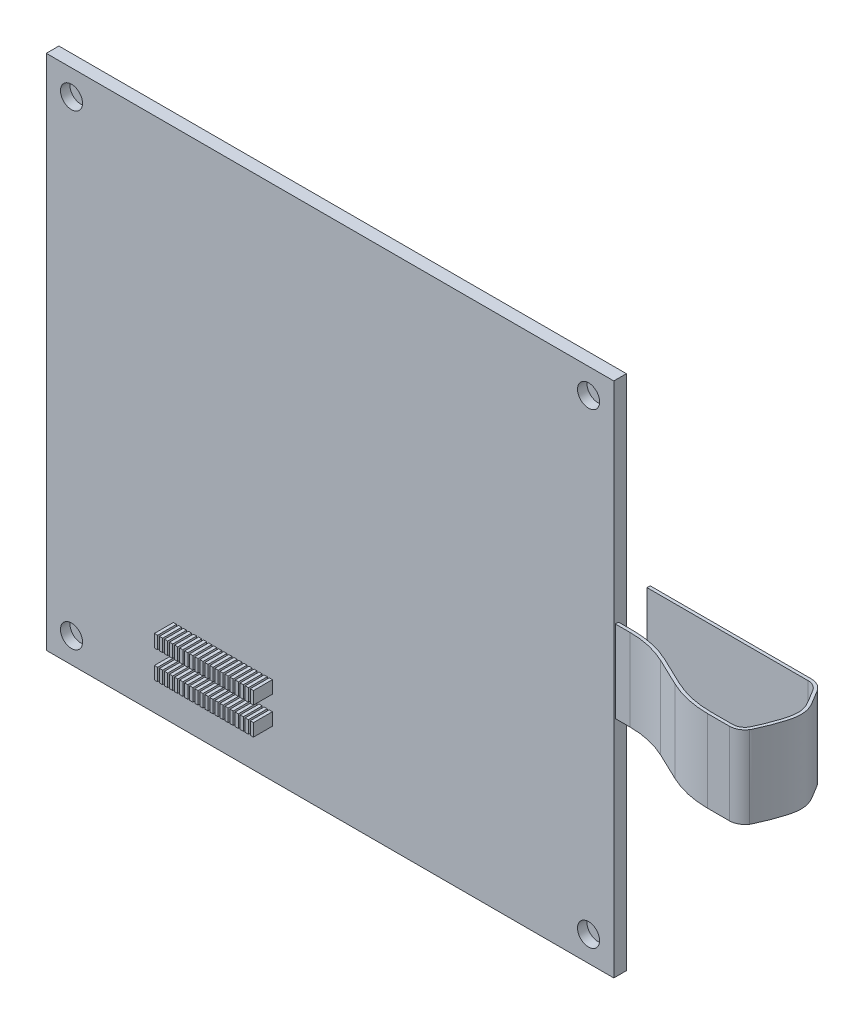
SolidWorks part; units mm, degrees
ref_plane "Face" through (0, 0, 0) normal (0, 0, 1) x (1, 0, 0)
ref_plane "Dessus" through (0, 0, 0) normal (0, 1, 0) x (1, 0, 0)
ref_plane "Droite" through (0, 0, 0) normal (1, 0, 0) x (0, 0, -1)
sketch "Esquisse1" plane through (0, 0, 0) normal (0, 0, 1) x (1, 0, 0)
  line L1 (0, 0) -> (90, 0)
  line L2 (0, 0) -> (0, 82)
  line L3 (0, 82) -> (90, 82)
  line L4 (90, 0) -> (90, 82)
  dimension "D1" = 90
  dimension "D2" = 82
extrude "Base-Extrusion" add sketch "Esquisse1" against normal blind 2
sketch "Esquisse2" plane through (0, 0, 0) normal (0, 0, 1) x (1, 0, 0)
  line L0 (90, 82) -> (0, 82) construction
  line L1 (0, 82) -> (0, 0) construction
  line L2 (90, 0) -> (90, 82) construction
  line L3 (0, 0) -> (90, 0) construction
  circle A0 centre (4, 78) radius 1.75
  circle A1 centre (86, 78) radius 1.75
  circle A2 centre (86, 4) radius 1.75
  circle A3 centre (4, 4) radius 1.75
  dimension "D1" = 3.5
  dimension "D2" = 3.5
  dimension "D3" = 3.5
  dimension "D4" = 3.5
  dimension "D6" = 4
  dimension "D7" = 4
  dimension "D8" = 4
  dimension "D9" = 4
  dimension "D10" = 4
  dimension "D11" = 4
  dimension "D12" = 4
  dimension "D5" = 4
extrude "Enlèv. mat.-Extru.1" cut sketch "Esquisse2" against normal blind 1.5
sketch "Esquisse3" plane through (0, 0, 0) normal (0, 0, 1) x (1, 0, 0)
  line L0 (20.4, 11.361) -> (20.4, 15.0274) construction
  line L1 (18.7961, 12.9) -> (22.2029, 12.9) construction
  line L2 (20.65, 13.9) -> (20.65, 11.9)
  line L3 (20.15, 13.9) -> (20.15, 11.9)
  line L4 (20.15, 13.9) -> (20.65, 13.9)
  line L5 (20.15, 11.9) -> (20.65, 11.9)
  line L6 (14.944, 10.7) -> (26.7013, 10.7) construction
  line L7 (20.15, 7.5) -> (20.65, 7.5)
  line L8 (35.6, 13.9) -> (35.6, 14.4408) construction
  line L10 (20.15, 9.5) -> (20.65, 9.5)
  line L11 (20.65, 9.5) -> (20.65, 7.5)
  line L12 (20.15, 9.5) -> (20.15, 7.5)
  line L13 (21.45, 13.9) -> (21.45, 11.9)
  line L14 (20.95, 13.9) -> (20.95, 11.9)
  line L15 (20.95, 13.9) -> (21.45, 13.9)
  line L16 (20.95, 11.9) -> (21.45, 11.9)
  line L17 (20.95, 7.5) -> (21.45, 7.5)
  line L20 (20.95, 9.5) -> (21.45, 9.5)
  line L21 (21.45, 9.5) -> (21.45, 7.5)
  line L22 (20.95, 9.5) -> (20.95, 7.5)
  line L23 (22.25, 13.9) -> (22.25, 11.9)
  line L24 (21.75, 13.9) -> (21.75, 11.9)
  line L25 (21.75, 13.9) -> (22.25, 13.9)
  line L26 (21.75, 11.9) -> (22.25, 11.9)
  line L27 (21.75, 7.5) -> (22.25, 7.5)
  line L30 (21.75, 9.5) -> (22.25, 9.5)
  line L31 (22.25, 9.5) -> (22.25, 7.5)
  line L32 (21.75, 9.5) -> (21.75, 7.5)
  line L33 (23.05, 13.9) -> (23.05, 11.9)
  line L34 (22.55, 13.9) -> (22.55, 11.9)
  line L35 (22.55, 13.9) -> (23.05, 13.9)
  line L36 (22.55, 11.9) -> (23.05, 11.9)
  line L37 (22.55, 7.5) -> (23.05, 7.5)
  line L40 (22.55, 9.5) -> (23.05, 9.5)
  line L41 (23.05, 9.5) -> (23.05, 7.5)
  line L42 (22.55, 9.5) -> (22.55, 7.5)
  line L43 (23.85, 13.9) -> (23.85, 11.9)
  line L44 (23.35, 13.9) -> (23.35, 11.9)
  line L45 (23.35, 13.9) -> (23.85, 13.9)
  line L46 (23.35, 11.9) -> (23.85, 11.9)
  line L47 (23.35, 7.5) -> (23.85, 7.5)
  line L50 (23.35, 9.5) -> (23.85, 9.5)
  line L51 (23.85, 9.5) -> (23.85, 7.5)
  line L52 (23.35, 9.5) -> (23.35, 7.5)
  line L53 (24.65, 13.9) -> (24.65, 11.9)
  line L54 (24.15, 13.9) -> (24.15, 11.9)
  line L55 (24.15, 13.9) -> (24.65, 13.9)
  line L56 (24.15, 11.9) -> (24.65, 11.9)
  line L57 (24.15, 7.5) -> (24.65, 7.5)
  line L60 (24.15, 9.5) -> (24.65, 9.5)
  line L61 (24.65, 9.5) -> (24.65, 7.5)
  line L62 (24.15, 9.5) -> (24.15, 7.5)
  line L63 (25.45, 13.9) -> (25.45, 11.9)
  line L64 (24.95, 13.9) -> (24.95, 11.9)
  line L65 (24.95, 13.9) -> (25.45, 13.9)
  line L66 (24.95, 11.9) -> (25.45, 11.9)
  line L67 (24.95, 7.5) -> (25.45, 7.5)
  line L70 (24.95, 9.5) -> (25.45, 9.5)
  line L71 (25.45, 9.5) -> (25.45, 7.5)
  line L72 (24.95, 9.5) -> (24.95, 7.5)
  line L73 (26.25, 13.9) -> (26.25, 11.9)
  line L74 (25.75, 13.9) -> (25.75, 11.9)
  line L75 (25.75, 13.9) -> (26.25, 13.9)
  line L76 (25.75, 11.9) -> (26.25, 11.9)
  line L77 (25.75, 7.5) -> (26.25, 7.5)
  line L80 (25.75, 9.5) -> (26.25, 9.5)
  line L81 (26.25, 9.5) -> (26.25, 7.5)
  line L82 (25.75, 9.5) -> (25.75, 7.5)
  line L83 (27.05, 13.9) -> (27.05, 11.9)
  line L84 (26.55, 13.9) -> (26.55, 11.9)
  line L85 (26.55, 13.9) -> (27.05, 13.9)
  line L86 (26.55, 11.9) -> (27.05, 11.9)
  line L87 (26.55, 7.5) -> (27.05, 7.5)
  line L90 (26.55, 9.5) -> (27.05, 9.5)
  line L91 (27.05, 9.5) -> (27.05, 7.5)
  line L92 (26.55, 9.5) -> (26.55, 7.5)
  line L93 (27.85, 13.9) -> (27.85, 11.9)
  line L94 (27.35, 13.9) -> (27.35, 11.9)
  line L95 (27.35, 13.9) -> (27.85, 13.9)
  line L96 (27.35, 11.9) -> (27.85, 11.9)
  line L97 (27.35, 7.5) -> (27.85, 7.5)
  line L100 (27.35, 9.5) -> (27.85, 9.5)
  line L101 (27.85, 9.5) -> (27.85, 7.5)
  line L102 (27.35, 9.5) -> (27.35, 7.5)
  line L103 (28.65, 13.9) -> (28.65, 11.9)
  line L104 (28.15, 13.9) -> (28.15, 11.9)
  line L105 (28.15, 13.9) -> (28.65, 13.9)
  line L106 (28.15, 11.9) -> (28.65, 11.9)
  line L107 (28.15, 7.5) -> (28.65, 7.5)
  line L110 (28.15, 9.5) -> (28.65, 9.5)
  line L111 (28.65, 9.5) -> (28.65, 7.5)
  line L112 (28.15, 9.5) -> (28.15, 7.5)
  line L113 (29.45, 13.9) -> (29.45, 11.9)
  line L114 (28.95, 13.9) -> (28.95, 11.9)
  line L115 (28.95, 13.9) -> (29.45, 13.9)
  line L116 (28.95, 11.9) -> (29.45, 11.9)
  line L117 (28.95, 7.5) -> (29.45, 7.5)
  line L120 (28.95, 9.5) -> (29.45, 9.5)
  line L121 (29.45, 9.5) -> (29.45, 7.5)
  line L122 (28.95, 9.5) -> (28.95, 7.5)
  line L123 (30.25, 13.9) -> (30.25, 11.9)
  line L124 (29.75, 13.9) -> (29.75, 11.9)
  line L125 (29.75, 13.9) -> (30.25, 13.9)
  line L126 (29.75, 11.9) -> (30.25, 11.9)
  line L127 (29.75, 7.5) -> (30.25, 7.5)
  line L130 (29.75, 9.5) -> (30.25, 9.5)
  line L131 (30.25, 9.5) -> (30.25, 7.5)
  line L132 (29.75, 9.5) -> (29.75, 7.5)
  line L133 (31.05, 13.9) -> (31.05, 11.9)
  line L134 (30.55, 13.9) -> (30.55, 11.9)
  line L135 (30.55, 13.9) -> (31.05, 13.9)
  line L136 (30.55, 11.9) -> (31.05, 11.9)
  line L137 (30.55, 7.5) -> (31.05, 7.5)
  line L140 (30.55, 9.5) -> (31.05, 9.5)
  line L141 (31.05, 9.5) -> (31.05, 7.5)
  line L142 (30.55, 9.5) -> (30.55, 7.5)
  line L143 (31.85, 13.9) -> (31.85, 11.9)
  line L144 (31.35, 13.9) -> (31.35, 11.9)
  line L145 (31.35, 13.9) -> (31.85, 13.9)
  line L146 (31.35, 11.9) -> (31.85, 11.9)
  line L147 (31.35, 7.5) -> (31.85, 7.5)
  line L150 (31.35, 9.5) -> (31.85, 9.5)
  line L151 (31.85, 9.5) -> (31.85, 7.5)
  line L152 (31.35, 9.5) -> (31.35, 7.5)
  line L153 (32.65, 13.9) -> (32.65, 11.9)
  line L154 (32.15, 13.9) -> (32.15, 11.9)
  line L155 (32.15, 13.9) -> (32.65, 13.9)
  line L156 (32.15, 11.9) -> (32.65, 11.9)
  line L157 (32.15, 7.5) -> (32.65, 7.5)
  line L160 (32.15, 9.5) -> (32.65, 9.5)
  line L161 (32.65, 9.5) -> (32.65, 7.5)
  line L162 (32.15, 9.5) -> (32.15, 7.5)
  line L163 (33.45, 13.9) -> (33.45, 11.9)
  line L164 (32.95, 13.9) -> (32.95, 11.9)
  line L165 (32.95, 13.9) -> (33.45, 13.9)
  line L166 (32.95, 11.9) -> (33.45, 11.9)
  line L167 (32.95, 7.5) -> (33.45, 7.5)
  line L170 (32.95, 9.5) -> (33.45, 9.5)
  line L171 (33.45, 9.5) -> (33.45, 7.5)
  line L172 (32.95, 9.5) -> (32.95, 7.5)
  line L173 (34.25, 13.9) -> (34.25, 11.9)
  line L174 (33.75, 13.9) -> (33.75, 11.9)
  line L175 (33.75, 13.9) -> (34.25, 13.9)
  line L176 (33.75, 11.9) -> (34.25, 11.9)
  line L177 (33.75, 7.5) -> (34.25, 7.5)
  line L180 (33.75, 9.5) -> (34.25, 9.5)
  line L181 (34.25, 9.5) -> (34.25, 7.5)
  line L182 (33.75, 9.5) -> (33.75, 7.5)
  line L183 (35.05, 13.9) -> (35.05, 11.9)
  line L184 (34.55, 13.9) -> (34.55, 11.9)
  line L185 (34.55, 13.9) -> (35.05, 13.9)
  line L186 (34.55, 11.9) -> (35.05, 11.9)
  line L187 (34.55, 7.5) -> (35.05, 7.5)
  line L190 (34.55, 9.5) -> (35.05, 9.5)
  line L191 (35.05, 9.5) -> (35.05, 7.5)
  line L192 (34.55, 9.5) -> (34.55, 7.5)
  line L193 (35.85, 13.9) -> (35.85, 11.9)
  line L194 (35.35, 13.9) -> (35.35, 11.9)
  line L195 (35.35, 13.9) -> (35.85, 13.9)
  line L196 (35.35, 11.9) -> (35.85, 11.9)
  line L197 (35.35, 7.5) -> (35.85, 7.5)
  line L200 (35.35, 9.5) -> (35.85, 9.5)
  line L201 (35.85, 9.5) -> (35.85, 7.5)
  line L202 (35.35, 9.5) -> (35.35, 7.5)
  circle A0 centre (4, 4) radius 1.75 construction
  dimension "D1" = 8.9
  dimension "D2" = 16.4
  dimension "D3" = 6.4
  dimension "D4" = 0.25
  dimension "D5" = 0.25
  dimension "D6" = 1
  dimension "D7" = 1
  dimension "D8" = 2
  dimension "D9" = 15.2
extrude "Boss.-Extru.1" add sketch "Esquisse3" along normal blind 3
sketch "Esquisse4" plane through (0, 0, 0) normal (0, 0, 1) x (1, 0, 0)
  line L0 (69.5396, 42.5) -> (94.6114, 42.5) construction
  circle A0 centre (86, 4) radius 1.75 construction
  dimension "D1" = 38.5
ref_plane "Plan1" through (0, 42, 0) normal (0, -1, 0) x (1, 0, 0)
sketch "Esquisse5" plane through (0, 42, 0) normal (0, -1, 0) x (1, 0, 0)
  line L0 (113.0642, 4.25) -> (109.6041, 4.25)
  line L2 (90, -0.75) -> (92.3472, -0.75)
  line L3 (103.1293, 2.7806) -> (98.822, 0.7194)
  line L4 (113.0589, -7.75) -> (87.5134, -7.75)
  line L5 (90, -0.25) -> (92.3472, -0.25)
  line L6 (102.9135, 3.2316) -> (98.6062, 1.1704)
  line L7 (113.0642, 4.75) -> (109.6041, 4.75)
  line L8 (113.0589, -8.25) -> (87.5134, -8.25)
  line L9 (90, -0.25) -> (90, -0.75)
  line L10 (87.5134, -7.75) -> (87.5134, -8.25)
  arc A0 (92.3472, -0.75) -> (98.822, 0.7194) centre (92.3472, 14.25) ccw
  arc A1 (103.1293, 2.7806) -> (109.6041, 4.25) centre (109.6041, -10.75) cw
  arc A2 (113.0589, -7.75) -> (114.7889, -6.7534) centre (113.0589, -5.75) ccw
  arc A3 (114.7904, 3.2601) -> (113.0642, 4.25) centre (113.0642, 2.25) ccw
  arc A4 (92.3472, -0.25) -> (98.6062, 1.1704) centre (92.3472, 14.25) ccw
  arc A5 (102.9135, 3.2316) -> (109.6041, 4.75) centre (109.6041, -10.75) cw
  arc A6 (115.145, 3.6358) -> (113.0642, 4.75) centre (113.0642, 2.25) ccw
  arc A7 (113.0589, -8.25) -> (115.2215, -7.0043) centre (113.0589, -5.75) ccw
  spline S0 degree 3 poles (114.7904, 3.2601) (114.5994, 3.6984) (117.8776, -3.0008) (115.9871, -4.6877) (114.7889, -6.7534) knots 0.083382 0.083382 0.083382 0.083382 0.500392 0.916953 0.916953 0.916953 0.916953
  spline S2 degree 3 poles (115.145, 3.6358) (115.1566, 3.6231) (115.1825, 3.5906) (115.1971, 3.568) (115.2139, 3.5412) (115.2268, 3.5169) (115.2523, 3.4682) (115.3209, 3.3274) (115.4864, 2.9733) (115.7603, 2.3529) (116.1839, 1.333) (116.7411, -0.1738) (117.1916, -1.9438) (117.1606, -3.3683) (116.7222, -4.5674) (116.1559, -5.4922) (115.6432, -6.2997) (115.3556, -6.773) (115.2215, -7.0043) knots 0.110985 0.110985 0.110985 0.110985 0.112559 0.114133 0.117282 0.123578 0.136171 0.161358 0.211731 0.262104 0.312477 0.413223 0.513969 0.614715 0.715461 0.816207 0.86658 0.916953 0.916953 0.916953 0.916953
  dimension "D2" = 15
  dimension "D4" = 2
  dimension "D3" = 7
extrude "Extrusion1" add sketch "Esquisse5" along normal blind 6.5 and the other way blind 6.5
